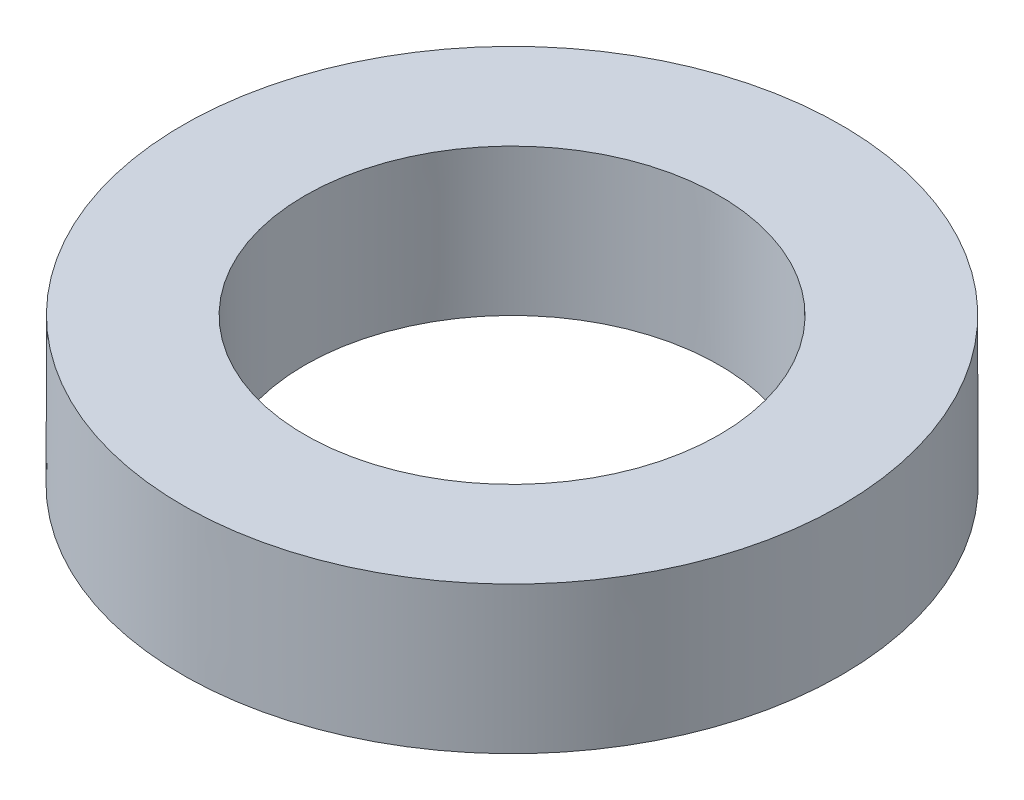
SolidWorks part; units mm, degrees
material "1.5805 (10NiCr5-4)"
ref_plane "Ön Düzlem" through (0, 0, 0) normal (0, 0, 1) x (1, 0, 0)
ref_plane "Üst Düzlem" through (0, 0, 0) normal (0, 1, 0) x (1, 0, 0)
ref_plane "Sağ Düzlem" through (0, 0, 0) normal (1, 0, 0) x (0, 0, -1)
sketch "Çizim1" plane through (0, 0, 0) normal (0, 0, 1) x (1, 0, 0)
  line L1 (9.7979, -0.0005) -> (15.5848, -0.0005)
  line L2 (15.5848, -0.0005) -> (15.5719, 6.9373)
  line L3 (15.5719, 6.9373) -> (9.7979, 6.9373)
  line L4 (9.7979, 6.9373) -> (9.7979, -0.0005)
  line L5 (0, 0) -> (0.0003, 6.9378) construction
  circle A0 centre (12.6849, 3.4684) radius 0.6642
revolve "Döndür1" add sketch "Çizim1" angle 360 about L5
